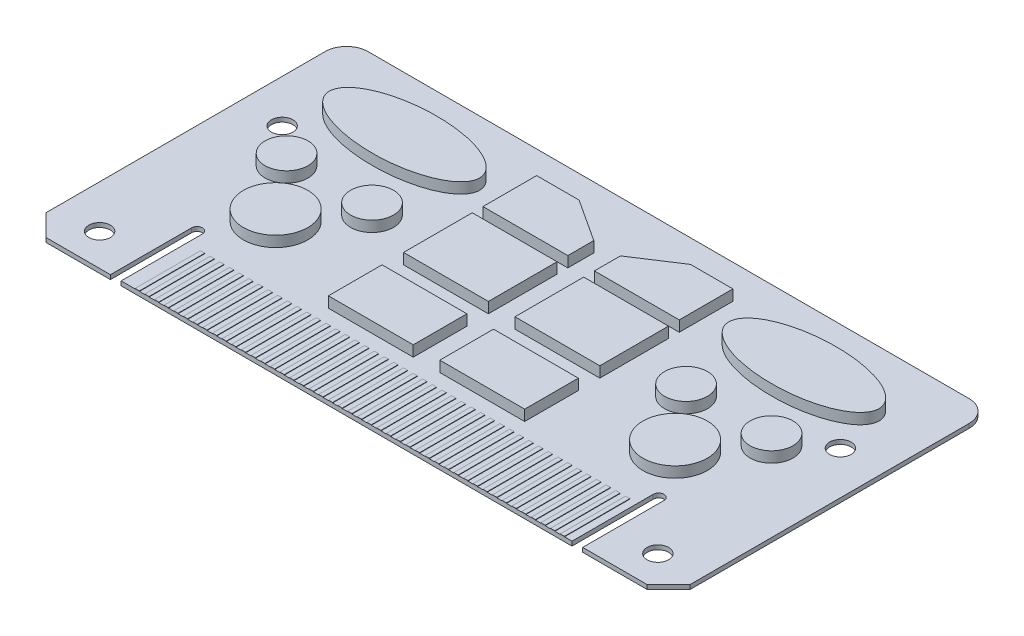
SolidWorks part; units mm, degrees
ref_plane "Front Plane" through (0, 0, 0) normal (0, 0, 1) x (1, 0, 0)
ref_plane "Top Plane" through (0, 0, 0) normal (0, 1, 0) x (1, 0, 0)
ref_plane "Right Plane" through (0, 0, 0) normal (1, 0, 0) x (0, 0, -1)
sketch "Sketch1" plane through (0, 0, 0) normal (0, 1, 0) x (1, 0, 0)
  line L1 (150, -75) -> (-150, -75)
  line L2 (150, -75) -> (150, 75)
  line L3 (150, 75) -> (-150, 75)
  line L4 (-150, -75) -> (-150, 75)
  line L5 (150, -75) -> (-150, 75) construction
  line L6 (150, 75) -> (-150, -75) construction
  line L40 (150, -75) -> (150, 75)
  line L41 (-150, -75) -> (-150, 75)
  point P0 (0, 0)
  point P16 (-35.3906, 40.3093)
  point P61 (0, 0)
  point P62 (0, 0)
  point P63 (0, 0)
  dimension "D1" = 150
  dimension "D2" = 300
extrude "Boss-Extrude3" add sketch "Sketch1" along normal blind 2 contours L4 L1 L2 L3
chamfer "Chamfer2" distance 10 angle 45 1 edges at (-150, 1, 75)
chamfer "Chamfer3" distance 10 angle 45 1 edges at (150, 1, 75)
fillet "Fillet1" radius 10 1 edges at (150, 1, -75)
fillet "Fillet2" radius 10 1 edges at (-150, 1, -75)
sketch "Sketch3" plane through (0, 2, 0) normal (0, 1, 0) x (1, 0, 0)
  line L0 (-150, -65) -> (-150, 65) construction
  line L1 (140, -75) -> (-140, -75) construction
  line L2 (0, 84.3463) -> (0, -93.4887) construction
  circle A0 centre (-130, -60) radius 5
  circle A1 centre (130, -60) radius 5
  dimension "D3" = 10
  dimension "D1" = 20
  dimension "D2" = 15
extrude "Cut-Extrude1" cut sketch "Sketch3" against normal through all
sketch "Sketch4" plane through (0, 2, 0) normal (0, 1, 0) x (1, 0, 0)
  line L2 (0, 86.7057) -> (0, -93.7837) construction
  circle A0 centre (-130, 25) radius 5
  circle A1 centre (130, 25) radius 5
  circle A2 centre (-130, -60) radius 5 construction
  dimension "D1" = 10
  dimension "D2" = 85
extrude "Cut-Extrude2" cut sketch "Sketch4" against normal through all
sketch "Sketch5" plane through (0, 2, 0) normal (0, 1, 0) x (1, 0, 0)
  line L0 (-107.5, -75) -> (-107.5, -37.1596) construction
  line L1 (140, -75) -> (-140, -75) construction
  line L2 (-110, -75) -> (-110, -37.1596)
  line L3 (-105, -75) -> (-105, -37.1596)
  line L4 (-150, -65) -> (-150, 65) construction
  line L5 (0, 81.0319) -> (0, -101.8168) construction
  line L6 (107.5, -75) -> (107.5, -37.1596) construction
  line L7 (110, -75) -> (110, -37.1596)
  line L8 (105, -75) -> (105, -37.1596)
  arc A0 (-110, -75) -> (-105, -75) centre (-107.5, -75) ccw
  arc A1 (-105, -37.1596) -> (-110, -37.1596) centre (-107.5, -37.1596) ccw
  arc A2 (110, -75) -> (105, -75) centre (107.5, -75) cw
  arc A3 (105, -37.1596) -> (110, -37.1596) centre (107.5, -37.1596) cw
  point P4 (-107.5, -56.0798)
  point P16 (107.5, -56.0798)
  dimension "D1" = 5
  dimension "D2" = 40
extrude "Cut-Extrude3" cut sketch "Sketch5" against normal through all
sketch "Sketch6" plane through (0, 2, 0) normal (0, 1, 0) x (1, 0, 0)
  line L1 (-110, -75) -> (-140, -75) construction
  line L2 (140, 75) -> (-140, 75) construction
  line L4 (0, 87.2955) -> (0, -102.0413) construction
  ellipse E0 centre (-93.0414, 45) end of major axis (-58.0414, 45) minor radius 15
  ellipse E1 centre (93.0414, 45) end of major axis (58.0414, 45) minor radius 15
  dimension "D1" = 135
  dimension "D2" = 70
  dimension "D3" = 45
extrude "Boss-Extrude4" add sketch "Sketch6" along normal blind 5 and the other way blind 5
sketch "Sketch7" plane through (0, 2, 0) normal (0, 1, 0) x (1, 0, 0)
  line L0 (140, 75) -> (-140, 75) construction
  line L1 (0, 85.526) -> (0, -94.6684) construction
  line L2 (-25.9527, 59.2506) -> (-6.1933, 46.3558)
  line L3 (-45.7122, 59.2506) -> (-25.9527, 59.2506)
  line L4 (-45.7122, 59.2506) -> (-45.7122, 34.2506)
  line L5 (-45.7122, 34.2506) -> (-6.1933, 34.2506)
  line L6 (-6.1933, 46.3558) -> (-6.1933, 34.2506)
  line L7 (-45.7122, 29.2506) -> (-6.1933, 29.2506)
  line L8 (-45.7122, 29.2506) -> (-45.7122, -2.7494)
  line L9 (-45.7122, -2.7494) -> (-6.1933, -2.7494)
  line L10 (-6.1933, 29.2506) -> (-6.1933, -2.7494)
  line L11 (-45.7122, -12.7494) -> (-6.1933, -12.7494)
  line L12 (-45.7122, -12.7494) -> (-45.7122, -37.7494)
  line L13 (-45.7122, -37.7494) -> (-6.1933, -37.7494)
  line L14 (-6.1933, -12.7494) -> (-6.1933, -37.7494)
  line L15 (45.7122, -37.7494) -> (6.1933, -37.7494)
  line L16 (6.1933, -12.7494) -> (6.1933, -37.7494)
  line L17 (45.7122, -12.7494) -> (6.1933, -12.7494)
  line L18 (45.7122, -12.7494) -> (45.7122, -37.7494)
  line L19 (45.7122, -2.7494) -> (6.1933, -2.7494)
  line L20 (6.1933, 29.2506) -> (6.1933, -2.7494)
  line L21 (45.7122, 29.2506) -> (6.1933, 29.2506)
  line L22 (45.7122, 29.2506) -> (45.7122, -2.7494)
  line L23 (45.7122, 59.2506) -> (25.9527, 59.2506)
  line L24 (45.7122, 59.2506) -> (45.7122, 34.2506)
  line L25 (45.7122, 34.2506) -> (6.1933, 34.2506)
  line L26 (6.1933, 46.3558) -> (6.1933, 34.2506)
  line L27 (25.9527, 59.2506) -> (6.1933, 46.3558)
  circle A0 centre (-112.9533, 10) radius 10
  circle A1 centre (-73.1295, 10) radius 10
  circle A2 centre (-93.0414, -15) radius 15
  circle A3 centre (112.9533, 10) radius 10
  circle A4 centre (93.0414, -15) radius 15
  circle A5 centre (73.1295, 10) radius 10
  point P21 (-25.9527, 29.2506)
  dimension "D1" = 20
  dimension "D2" = 65
  dimension "D3" = 30
  dimension "D4" = 90
  dimension "D5" = 25
  dimension "D6" = 5
  dimension "D7" = 32
  dimension "D8" = 25
  dimension "D9" = 10
extrude "Boss-Extrude5" add sketch "Sketch7" along normal blind 5 and the other way blind 5
sketch "Sketch12" plane through (0, 2, 0) normal (0, 1, 0) x (1, 0, 0)
  line L0 (105, -75) -> (-105, -75) construction
  line L1 (-98.5, -75) -> (-96.5, -75)
  line L2 (-98.5, -75) -> (-98.5, -44.5325)
  line L3 (-98.5, -44.5325) -> (-96.5, -44.5325)
  line L4 (-96.5, -75) -> (-96.5, -44.5325)
  line L5 (-105, -75) -> (-105, -37.1596) construction
  line L6 (-94, -75) -> (-94, -44.5325)
  line L7 (-94, -75) -> (-92, -75)
  line L8 (-92, -75) -> (-92, -44.5325)
  line L9 (-94, -44.5325) -> (-92, -44.5325)
  line L10 (-89.5, -75) -> (-89.5, -44.5325)
  line L11 (-89.5, -75) -> (-87.5, -75)
  line L12 (-87.5, -75) -> (-87.5, -44.5325)
  line L13 (-89.5, -44.5325) -> (-87.5, -44.5325)
  line L14 (-85, -75) -> (-85, -44.5325)
  line L15 (-85, -75) -> (-83, -75)
  line L16 (-83, -75) -> (-83, -44.5325)
  line L17 (-85, -44.5325) -> (-83, -44.5325)
  line L18 (-80.5, -75) -> (-80.5, -44.5325)
  line L19 (-80.5, -75) -> (-78.5, -75)
  line L20 (-78.5, -75) -> (-78.5, -44.5325)
  line L21 (-80.5, -44.5325) -> (-78.5, -44.5325)
  line L22 (-76, -75) -> (-76, -44.5325)
  line L23 (-76, -75) -> (-74, -75)
  line L24 (-74, -75) -> (-74, -44.5325)
  line L25 (-76, -44.5325) -> (-74, -44.5325)
  line L26 (-71.5, -75) -> (-71.5, -44.5325)
  line L27 (-71.5, -75) -> (-69.5, -75)
  line L28 (-69.5, -75) -> (-69.5, -44.5325)
  line L29 (-71.5, -44.5325) -> (-69.5, -44.5325)
  line L30 (-67, -75) -> (-67, -44.5325)
  line L31 (-67, -75) -> (-65, -75)
  line L32 (-65, -75) -> (-65, -44.5325)
  line L33 (-67, -44.5325) -> (-65, -44.5325)
  line L34 (-62.5, -75) -> (-62.5, -44.5325)
  line L35 (-62.5, -75) -> (-60.5, -75)
  line L36 (-60.5, -75) -> (-60.5, -44.5325)
  line L37 (-62.5, -44.5325) -> (-60.5, -44.5325)
  line L38 (-58, -75) -> (-58, -44.5325)
  line L39 (-58, -75) -> (-56, -75)
  line L40 (-56, -75) -> (-56, -44.5325)
  line L41 (-58, -44.5325) -> (-56, -44.5325)
  line L42 (-53.5, -75) -> (-53.5, -44.5325)
  line L43 (-53.5, -75) -> (-51.5, -75)
  line L44 (-51.5, -75) -> (-51.5, -44.5325)
  line L45 (-53.5, -44.5325) -> (-51.5, -44.5325)
  line L46 (-49, -75) -> (-49, -44.5325)
  line L47 (-49, -75) -> (-47, -75)
  line L48 (-47, -75) -> (-47, -44.5325)
  line L49 (-49, -44.5325) -> (-47, -44.5325)
  line L50 (-44.5, -75) -> (-44.5, -44.5325)
  line L51 (-44.5, -75) -> (-42.5, -75)
  line L52 (-42.5, -75) -> (-42.5, -44.5325)
  line L53 (-44.5, -44.5325) -> (-42.5, -44.5325)
  line L54 (-40, -75) -> (-40, -44.5325)
  line L55 (-40, -75) -> (-38, -75)
  line L56 (-38, -75) -> (-38, -44.5325)
  line L57 (-40, -44.5325) -> (-38, -44.5325)
  line L58 (-35.5, -75) -> (-35.5, -44.5325)
  line L59 (-35.5, -75) -> (-33.5, -75)
  line L60 (-33.5, -75) -> (-33.5, -44.5325)
  line L61 (-35.5, -44.5325) -> (-33.5, -44.5325)
  line L62 (-31, -75) -> (-31, -44.5325)
  line L63 (-31, -75) -> (-29, -75)
  line L64 (-29, -75) -> (-29, -44.5325)
  line L65 (-31, -44.5325) -> (-29, -44.5325)
  line L66 (-26.5, -75) -> (-26.5, -44.5325)
  line L67 (-26.5, -75) -> (-24.5, -75)
  line L68 (-24.5, -75) -> (-24.5, -44.5325)
  line L69 (-26.5, -44.5325) -> (-24.5, -44.5325)
  line L70 (-22, -75) -> (-22, -44.5325)
  line L71 (-22, -75) -> (-20, -75)
  line L72 (-20, -75) -> (-20, -44.5325)
  line L73 (-22, -44.5325) -> (-20, -44.5325)
  line L74 (-17.5, -75) -> (-17.5, -44.5325)
  line L75 (-17.5, -75) -> (-15.5, -75)
  line L76 (-15.5, -75) -> (-15.5, -44.5325)
  line L77 (-17.5, -44.5325) -> (-15.5, -44.5325)
  line L78 (-13, -75) -> (-13, -44.5325)
  line L79 (-13, -75) -> (-11, -75)
  line L80 (-11, -75) -> (-11, -44.5325)
  line L81 (-13, -44.5325) -> (-11, -44.5325)
  line L82 (-8.5, -75) -> (-8.5, -44.5325)
  line L83 (-8.5, -75) -> (-6.5, -75)
  line L84 (-6.5, -75) -> (-6.5, -44.5325)
  line L85 (-8.5, -44.5325) -> (-6.5, -44.5325)
  line L86 (-4, -75) -> (-4, -44.5325)
  line L87 (-4, -75) -> (-2, -75)
  line L88 (-2, -75) -> (-2, -44.5325)
  line L89 (-4, -44.5325) -> (-2, -44.5325)
  line L90 (0.5, -75) -> (0.5, -44.5325)
  line L91 (0.5, -75) -> (2.5, -75)
  line L92 (2.5, -75) -> (2.5, -44.5325)
  line L93 (0.5, -44.5325) -> (2.5, -44.5325)
  line L94 (5, -75) -> (5, -44.5325)
  line L95 (5, -75) -> (7, -75)
  line L96 (7, -75) -> (7, -44.5325)
  line L97 (5, -44.5325) -> (7, -44.5325)
  line L98 (9.5, -75) -> (9.5, -44.5325)
  line L99 (9.5, -75) -> (11.5, -75)
  line L100 (11.5, -75) -> (11.5, -44.5325)
  line L101 (9.5, -44.5325) -> (11.5, -44.5325)
  line L102 (14, -75) -> (14, -44.5325)
  line L103 (14, -75) -> (16, -75)
  line L104 (16, -75) -> (16, -44.5325)
  line L105 (14, -44.5325) -> (16, -44.5325)
  line L106 (18.5, -75) -> (18.5, -44.5325)
  line L107 (18.5, -75) -> (20.5, -75)
  line L108 (20.5, -75) -> (20.5, -44.5325)
  line L109 (18.5, -44.5325) -> (20.5, -44.5325)
  line L110 (23, -75) -> (23, -44.5325)
  line L111 (23, -75) -> (25, -75)
  line L112 (25, -75) -> (25, -44.5325)
  line L113 (23, -44.5325) -> (25, -44.5325)
  line L114 (27.5, -75) -> (27.5, -44.5325)
  line L115 (27.5, -75) -> (29.5, -75)
  line L116 (29.5, -75) -> (29.5, -44.5325)
  line L117 (27.5, -44.5325) -> (29.5, -44.5325)
  line L118 (32, -75) -> (32, -44.5325)
  line L119 (32, -75) -> (34, -75)
  line L120 (34, -75) -> (34, -44.5325)
  line L121 (32, -44.5325) -> (34, -44.5325)
  line L122 (36.5, -75) -> (36.5, -44.5325)
  line L123 (36.5, -75) -> (38.5, -75)
  line L124 (38.5, -75) -> (38.5, -44.5325)
  line L125 (36.5, -44.5325) -> (38.5, -44.5325)
  line L126 (41, -75) -> (41, -44.5325)
  line L127 (41, -75) -> (43, -75)
  line L128 (43, -75) -> (43, -44.5325)
  line L129 (41, -44.5325) -> (43, -44.5325)
  line L130 (45.5, -75) -> (45.5, -44.5325)
  line L131 (45.5, -75) -> (47.5, -75)
  line L132 (47.5, -75) -> (47.5, -44.5325)
  line L133 (45.5, -44.5325) -> (47.5, -44.5325)
  line L134 (50, -75) -> (50, -44.5325)
  line L135 (50, -75) -> (52, -75)
  line L136 (52, -75) -> (52, -44.5325)
  line L137 (50, -44.5325) -> (52, -44.5325)
  line L138 (54.5, -75) -> (54.5, -44.5325)
  line L139 (54.5, -75) -> (56.5, -75)
  line L140 (56.5, -75) -> (56.5, -44.5325)
  line L141 (54.5, -44.5325) -> (56.5, -44.5325)
  line L142 (59, -75) -> (59, -44.5325)
  line L143 (59, -75) -> (61, -75)
  line L144 (61, -75) -> (61, -44.5325)
  line L145 (59, -44.5325) -> (61, -44.5325)
  line L146 (63.5, -75) -> (63.5, -44.5325)
  line L147 (63.5, -75) -> (65.5, -75)
  line L148 (65.5, -75) -> (65.5, -44.5325)
  line L149 (63.5, -44.5325) -> (65.5, -44.5325)
  line L150 (68, -75) -> (68, -44.5325)
  line L151 (68, -75) -> (70, -75)
  line L152 (70, -75) -> (70, -44.5325)
  line L153 (68, -44.5325) -> (70, -44.5325)
  line L154 (72.5, -75) -> (72.5, -44.5325)
  line L155 (72.5, -75) -> (74.5, -75)
  line L156 (74.5, -75) -> (74.5, -44.5325)
  line L157 (72.5, -44.5325) -> (74.5, -44.5325)
  line L158 (77, -75) -> (77, -44.5325)
  line L159 (77, -75) -> (79, -75)
  line L160 (79, -75) -> (79, -44.5325)
  line L161 (77, -44.5325) -> (79, -44.5325)
  line L162 (81.5, -75) -> (81.5, -44.5325)
  line L163 (81.5, -75) -> (83.5, -75)
  line L164 (83.5, -75) -> (83.5, -44.5325)
  line L165 (81.5, -44.5325) -> (83.5, -44.5325)
  line L166 (86, -75) -> (86, -44.5325)
  line L167 (86, -75) -> (88, -75)
  line L168 (88, -75) -> (88, -44.5325)
  line L169 (86, -44.5325) -> (88, -44.5325)
  line L170 (90.5, -75) -> (90.5, -44.5325)
  line L171 (90.5, -75) -> (92.5, -75)
  line L172 (92.5, -75) -> (92.5, -44.5325)
  line L173 (90.5, -44.5325) -> (92.5, -44.5325)
  line L174 (95, -75) -> (95, -44.5325)
  line L175 (95, -75) -> (97, -75)
  line L176 (97, -75) -> (97, -44.5325)
  line L177 (95, -44.5325) -> (97, -44.5325)
  line L178 (99.5, -75) -> (99.5, -44.5325)
  line L179 (99.5, -75) -> (101.5, -75)
  line L180 (101.5, -75) -> (101.5, -44.5325)
  line L181 (99.5, -44.5325) -> (101.5, -44.5325)
  line L182 (-98.5, -75) -> (-94, -75) construction
  point P8 (-96.5, -59.7662)
  dimension "D1" = 6.5
  dimension "D2" = 2
  dimension "D3" = 30.4675
  dimension "D5" = 4.5
  dimension "D4" = 45
extrude "Boss-Extrude6" add sketch "Sketch12" along normal blind 0.2 and the other way blind 0.2 separate body
